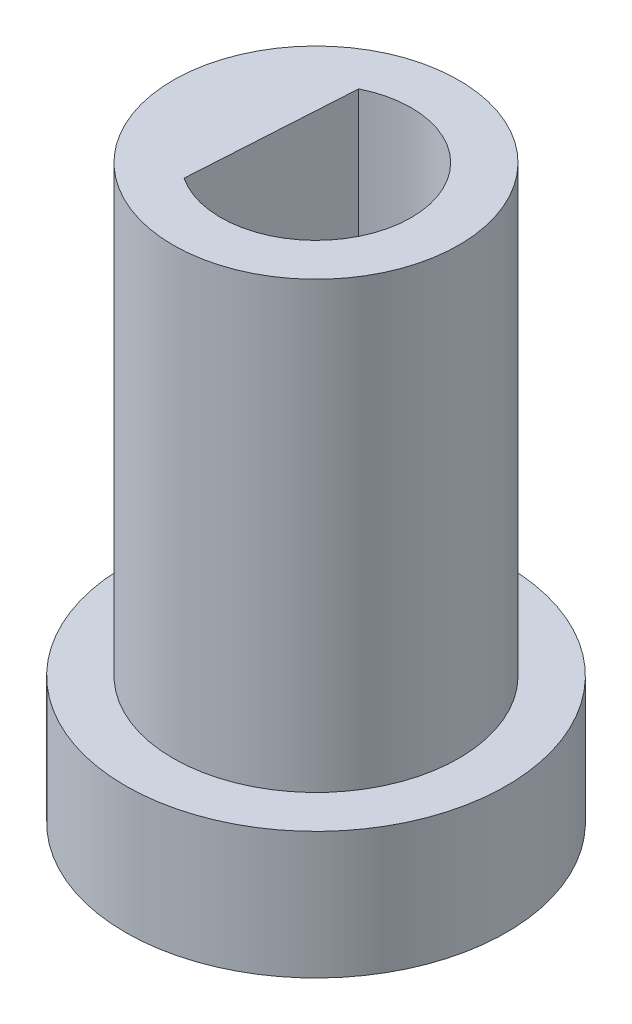
SolidWorks part; units mm, degrees
ref_plane "Front Plane" through (0, 0, 0) normal (0, 0, 1) x (1, 0, 0)
ref_plane "Top Plane" through (0, 0, 0) normal (0, 1, 0) x (1, 0, 0)
ref_plane "Right Plane" through (0, 0, 0) normal (1, 0, 0) x (0, 0, -1)
sketch "Sketch1" plane through (0, 0, 0) normal (0, 1, 0) x (1, 0, 0)
  circle A0 centre (0, 0) radius 6
  dimension "D1" = 12
extrude "Boss-Extrude1" add sketch "Sketch1" along normal blind 4
sketch "Sketch2" plane through (0, 4, 0) normal (0, 1, 0) x (1, 0, 0)
  circle A0 centre (0, 0) radius 4.5
  dimension "D1" = 9
extrude "Boss-Extrude2" add sketch "Sketch2" along normal blind 14
sketch "Sketch3" plane through (0, 0, 0) normal (0, -1, 0) x (-1, 0, 0)
  line L1 (2.5, 2.5) -> (-2.5, 2.5)
  line L2 (2.5, 2.5) -> (2.5, -2.5)
  line L3 (2.5, -2.5) -> (-2.5, -2.5)
  line L4 (-2.5, 2.5) -> (-2.5, -2.5)
  line L5 (2.5, 2.5) -> (-2.5, -2.5) construction
  line L6 (2.5, -2.5) -> (-2.5, 2.5) construction
  point P0 (0, 0)
  dimension "D1" = 5
  dimension "D2" = 5
extrude "Cut-Extrude1" cut sketch "Sketch3" against normal blind 4
sketch "Sketch4" plane through (0, 18, 0) normal (0, 1, 0) x (1, 0, 0)
  circle A0 centre (0, 0) radius 3
  dimension "D1" = 6
extrude "Cut-Extrude2" cut sketch "Sketch4" against normal blind 10
sketch "Sketch5" plane through (0, 8, 0) normal (0, 1, 0) x (1, 0, 0)
  line L0 (-1.3396, 2.6843) -> (-1.6549, -2.5023)
  circle A0 centre (0, 0) radius 3 construction
  circle A1 centre (0, 0) radius 3
  circle M2 centre (0, 0) radius 3
  dimension "D1" = 1.5
extrude "Boss-Extrude3" add sketch "Sketch5" along normal blind 10 contours L0 M2
